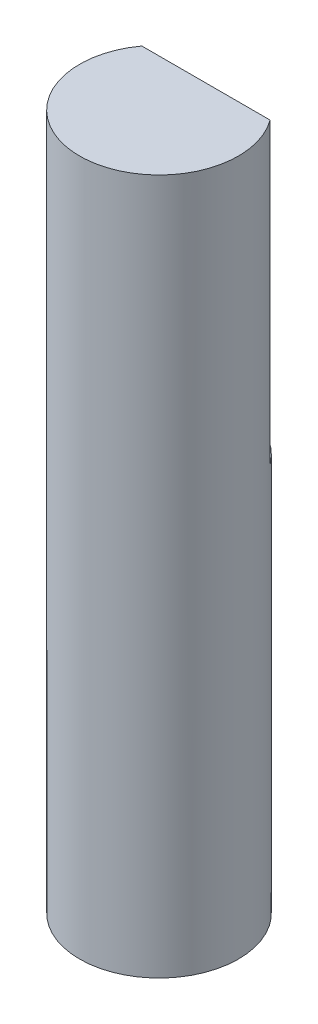
SolidWorks part; units mm, degrees
ref_plane "Front Plane" through (0, 0, 0) normal (0, 0, 1) x (1, 0, 0)
ref_plane "Top Plane" through (0, 0, 0) normal (0, 1, 0) x (1, 0, 0)
ref_plane "Right Plane" through (0, 0, 0) normal (1, 0, 0) x (0, 0, -1)
sketch "Sketch1" plane through (0, 0, 0) normal (0, 1, 0) x (1, 0, 0)
  line L0 (-4.0996, 3) -> (4.0996, 3)
  arc A0 (-4.0996, 3) -> (4.0996, 3) centre (0, 0) ccw
  dimension "D1" = 10.16
  dimension "D2" = 3
extrude "Boss-Extrude1" add sketch "Sketch1" along normal blind 44.45
sketch "Sketch3" plane through (0, 0, 0) normal (0, -1, 0) x (1, 0, 0)
  line L0 (-4.0996, -3) -> (4.0996, -3)
  arc A0 (-4.0996, -3) -> (4.0996, -3) centre (0, 0) ccw
extrude "Boss-Extrude2" add sketch "Sketch3" against normal blind 25.4
